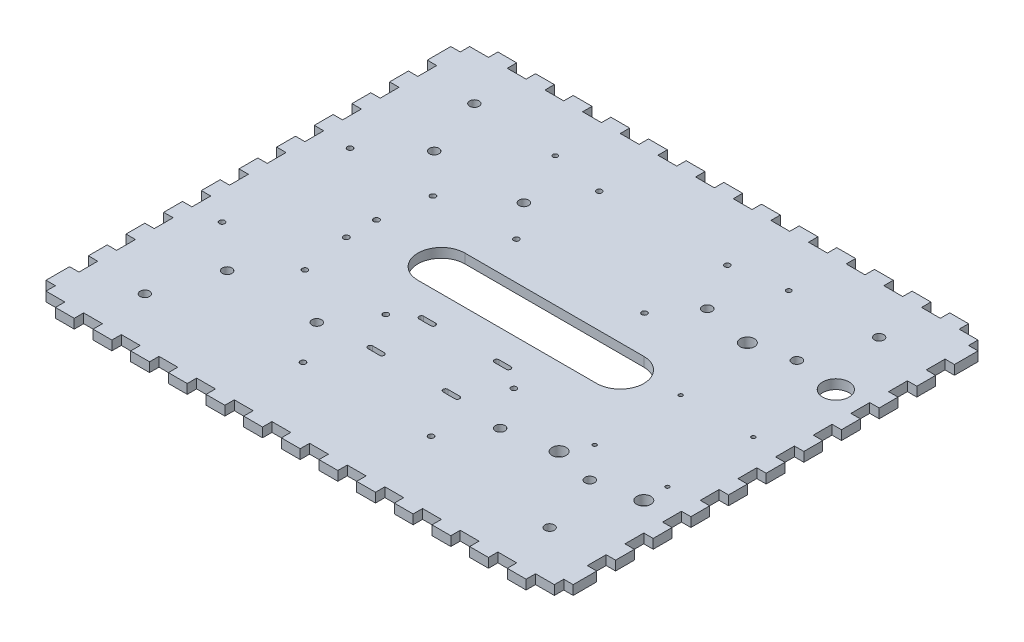
SolidWorks part; units mm, degrees
material "Acrylic (Medium-high impact)"
ref_plane "Front Plane" through (0, 0, 0) normal (0, 0, 1) x (1, 0, 0)
ref_plane "Top Plane" through (0, 0, 0) normal (0, 1, 0) x (1, 0, 0)
ref_plane "Right Plane" through (0, 0, 0) normal (1, 0, 0) x (0, 0, -1)
sketch "Sketch1" plane through (0, 0, 0) normal (0, 1, 0) x (1, 0, 0)
  line L0 (-144.4625, -95.25) -> (-42.8625, -95.25) construction
  line L2 (-174.625, -152.4) -> (-174.625, -139.7) construction
  line L3 (-174.625, 152.4) -> (-161.925, 152.4) construction
  line L4 (174.625, -152.4) -> (174.625, -133.5516) construction
  line L5 (-174.625, -152.4) -> (174.625, 152.4) construction
  line L6 (-174.625, 152.4) -> (174.625, -152.4) construction
  line L7 (-93.6625, -93.6625) -> (93.6625, -93.6625) construction
  line L8 (-93.6625, -93.6625) -> (-93.6625, 93.6625) construction
  line L9 (-93.6625, 93.6625) -> (93.6625, 93.6625) construction
  line L10 (93.6625, -93.6625) -> (93.6625, 93.6625) construction
  line L11 (-93.6625, -93.6625) -> (93.6625, 93.6625) construction
  line L12 (-93.6625, 93.6625) -> (93.6625, -93.6625) construction
  line L13 (42.8625, -95.25) -> (144.4625, -95.25) construction
  line L14 (-93.6625, -95.25) -> (-93.6625, -1.8183) construction
  line L15 (93.6625, -95.25) -> (93.6625, -91.9321) construction
  line L16 (-177.8, 0) -> (168.5824, 0) construction
  line L17 (42.8625, 95.25) -> (144.4625, 95.25) construction
  line L18 (93.6625, 95.25) -> (93.6625, 91.9321) construction
  line L19 (-93.6625, 95.25) -> (-93.6625, -1.8183) construction
  line L20 (-144.4625, 95.25) -> (-42.8625, 95.25) construction
  line L21 (-174.625, -152.4) -> (-161.925, -152.4) construction
  line L22 (-144.4625, 95.25) -> (-42.8625, 95.25) construction
  line L23 (-144.4625, 95.25) -> (-144.4625, 142.24) construction
  line L24 (-144.4625, 142.24) -> (-44.45, 142.24) construction
  line L26 (42.8625, 95.25) -> (144.4625, 95.25) construction
  line L28 (44.45, 142.24) -> (144.4625, 142.24) construction
  line L29 (144.4625, 95.25) -> (144.4625, 142.24) construction
  line L30 (44.45, 142.24) -> (-44.45, 142.24) construction
  line L31 (-144.4625, -95.25) -> (-42.8625, -95.25) construction
  line L33 (-144.4625, -142.24) -> (-42.8625, -142.24) construction
  line L34 (-42.8625, -95.25) -> (-42.8625, -142.24) construction
  line L35 (42.8625, -95.25) -> (144.4625, -95.25) construction
  line L36 (42.8625, -95.25) -> (42.8625, -142.24) construction
  line L37 (42.8625, -142.24) -> (144.4625, -142.24) construction
  line L43 (-110.3714, 54.9124) -> (-110.3714, 5.6364) construction
  line L44 (0.7937, 148.8037) -> (0.7938, -148.6976) construction
  line L45 (-174.625, 139.7) -> (-174.625, 152.4) construction
  line L46 (174.625, 133.5516) -> (174.625, 152.4) construction
  line L49 (163.5125, -152.4) -> (174.625, -152.4) construction
  line L50 (163.5125, 152.4) -> (174.625, 152.4) construction
  line L51 (144.4625, -95.25) -> (172.1593, -95.25) construction
  line L56 (156.9193, 27.9999) -> (71.9193, 27.9999) construction
  line L58 (-31.75, -142.24) -> (31.75, -142.24) construction
  line L62 (156.9193, 27.9999) -> (156.9193, -28.0001) construction
  line L64 (42.8625, -142.24) -> (-42.8625, -142.24) construction
  line L65 (-144.4625, -95.25) -> (-170.5718, -95.25) construction
  line L66 (-144.4625, 95.25) -> (-170.5718, 95.25) construction
  line L67 (144.4625, 95.25) -> (172.1593, 95.25) construction
  line L69 (-30.9562, -134.62) -> (32.5438, -134.62) construction
  line L73 (42.8625, 95.25) -> (-42.8625, 95.25) construction
  line L74 (42.8625, -95.25) -> (-42.8625, -95.25) construction
  line L75 (156.9193, -28.0001) -> (71.9193, -28.0001) construction
  line L76 (71.9193, 27.9999) -> (71.9193, -28.0001) construction
  line L81 (-113.5464, 54.9124) -> (-75.9544, 54.9124) construction
  line L82 (-113.5464, 54.9124) -> (-113.5464, 5.6364) construction
  line L83 (-113.5464, 5.6364) -> (-75.9544, 5.6364) construction
  line L84 (-75.9544, 54.9124) -> (-75.9544, 5.6364) construction
  line L85 (-79.1294, 5.6364) -> (-79.1294, 54.9124) construction
  line L87 (-177.8, -149.225) -> (177.8, -149.225)
  line L88 (-177.8, -149.225) -> (-177.8, 149.225)
  line L89 (-177.8, 149.225) -> (177.8, 149.225)
  line L90 (177.8, -149.225) -> (177.8, 149.225)
  line L91 (-177.8, -149.225) -> (177.8, 149.225) construction
  line L92 (-177.8, 149.225) -> (177.8, -149.225) construction
  arc A56 (-160.8077, 152.3508) -> (-174.5495, 138.3168) centre (-161.925, 139.7) ccw construction
  arc A57 (-160.7914, -152.3493) -> (-174.5495, -138.3168) centre (-161.925, -139.7) cw construction
  arc A58 (-174.5495, 138.3168) -> (-174.5495, -138.3168) centre (-1436.9949, 0) cw construction
  arc A59 (162.3789, -152.3493) -> (176.137, -138.3168) centre (163.5125, -139.7) ccw construction
  arc A60 (176.137, 138.3168) -> (176.137, -138.3168) centre (1438.5824, 0) ccw construction
  arc A61 (162.3952, 152.3508) -> (176.137, 138.3168) centre (163.5125, 139.7) cw construction
  arc A62 (-161.925, 152.4) -> (163.5125, 152.4) centre (0.7937, 3831.8037) ccw construction
  circle A64 centre (-161.925, 139.7) radius 1.8415 construction
  circle A65 centre (-161.925, -139.7) radius 1.8415 construction
  circle A66 centre (163.5125, -139.7) radius 1.8415 construction
  circle A67 centre (163.5125, 139.7) radius 1.8415 construction
  circle A82 centre (163.5125, 96.52) radius 1.8415 construction
  circle A84 centre (163.5125, -96.52) radius 1.8415 construction
  arc A88 (-170.5718, -95.25) -> (-170.5718, 95.25) centre (-1436.9949, 0) ccw construction
  arc A89 (172.1593, 95.25) -> (172.1593, -95.25) centre (1438.5824, 0) ccw construction
  circle A90 centre (-26.3525, -130.81) radius 1.905 construction
  circle A91 centre (29.5275, -130.81) radius 1.905 construction
  circle A98 centre (0, 0) radius 1.8415 construction
  circle A99 centre (-157.8718, 82.55) radius 1.8415 construction
  circle A100 centre (-157.8718, -82.55) radius 1.8415 construction
  circle A101 centre (159.4593, -82.55) radius 1.8415 construction
  circle A102 centre (159.4593, 82.55) radius 1.8415 construction
  circle A103 centre (-53.34, 0) radius 1.8415 construction
  circle A104 centre (-106.68, 0) radius 1.8415 construction
  circle A105 centre (-160.02, 0) radius 1.8415 construction
  circle A106 centre (-5.4718, -85.8596) radius 1.8415 construction
  circle A107 centre (7.0593, -85.8596) radius 1.8415 construction
  circle A108 centre (-8.6468, 82.55) radius 1.8415 construction
  circle A109 centre (10.2343, 82.55) radius 1.8415 construction
  circle A110 centre (75.4193, -24.5001) radius 1.651 construction
  circle A111 centre (75.4193, 24.5001) radius 1.651 construction
  circle A112 centre (133.4193, 24.5001) radius 1.651 construction
  circle A113 centre (133.4193, -24.5001) radius 1.651 construction
  circle A114 centre (-110.3714, 48.6894) radius 1.651 construction
  circle A115 centre (-110.3714, 42.3394) radius 1.651 construction
  circle A116 centre (-110.3714, 35.9894) radius 1.651 construction
  circle A117 centre (-110.3714, 29.6394) radius 1.651 construction
  circle A118 centre (-110.3714, 23.2894) radius 1.651 construction
  circle A119 centre (-110.3714, 16.9394) radius 1.651 construction
  circle A120 centre (-110.3714, 10.5894) radius 1.651 construction
  circle A121 centre (-79.1294, 48.6894) radius 1.651 construction
  circle A122 centre (-79.1294, 42.3394) radius 1.651 construction
  circle A123 centre (-79.1294, 35.9894) radius 1.651 construction
  circle A124 centre (-79.1294, 29.6394) radius 1.651 construction
  circle A125 centre (-79.1294, 23.2894) radius 1.651 construction
  circle A126 centre (-79.1294, 10.5894) radius 1.651 construction
  circle A127 centre (-79.1294, 16.9394) radius 1.651 construction
  circle A128 centre (-101.6, 10.16) radius 1.905
  circle A129 centre (-101.6, -10.16) radius 1.905
  point P0 (0, 0)
  point P6 (0, 0)
  point P37 (-93.6625, 79.4385)
  point P51 (-94.7504, 54.9124)
  point P188 (93.6625, 0)
  point P205 (0, -93.6625)
  dimension "D17" = 3.5
  dimension "D19" = 58
  dimension "D21" = 25.4
  dimension "D22" = 1270
  dimension "D23" = 3683
  dimension "D24" = 3.683
  dimension "D25" = 3.683
  dimension "D26" = 3.683
  dimension "D27" = 3.683
  dimension "D31" = 152.4
  dimension "D50" = 3.683
  dimension "D51" = 3.81
  dimension "D52" = 3.81
  dimension "D57" = 3.683
  dimension "D60" = 4
  dimension "D18" = 3.302
  dimension "D20" = 3.302
  dimension "D30" = 3.683
  dimension "D32" = 355.6
  dimension "D34" = 76.2
  dimension "D38" = 3.81
  dimension "D39" = 3.81
  dimension "D1" = 349.25
  dimension "D2" = 304.8
  dimension "D3" = 101.6
  dimension "D4" = 101.6
  dimension "D5" = 187.325
  dimension "D6" = 190.5
  dimension "D7" = 190.5
  dimension "D8" = 46.99
  dimension "D9" = 46.99
  dimension "D10" = 46.99
  dimension "D11" = 46.99
  dimension "D12" = 85
  dimension "D13" = 56
  dimension "D14" = 27.9999
  dimension "D15" = 15.24
  dimension "D16" = 3.5
  dimension "D28" = 4.953
  dimension "D29" = 6.35
  dimension "D33" = 298.45
  dimension "D35" = 76.2
  dimension "D36" = 20.32
  dimension "D37" = 139.065
  dimension "D40" = 63.5
  dimension "D41" = 31.75
  dimension "D43" = 7.62
  dimension "D44" = 46.99
  dimension "D45" = 19.05
  dimension "D46" = 45.72
  dimension "D47" = 19.05
  dimension "D53" = 3.81
  dimension "D55" = 3.81
  dimension "D58" = 12.7
  dimension "D59" = 12.7
  dimension "D61" = 53.34
extrude "Boss-Extrude1" add sketch "Sketch1" along normal blind 6.35
sketch "Sketch2" plane through (0, 6.35, 0) normal (0, 1, 0) x (1, 0, 0)
  line L0 (-61.8382, 69.85) -> (-122.3118, 69.85) construction
  line L1 (0, 0) -> (-61.8382, 0) construction
  line L2 (-61.8382, 0) -> (-61.8382, 69.85) construction
  line L4 (-61.8382, 0) -> (-61.8382, -69.85) construction
  line L5 (-61.8382, -69.85) -> (-122.3118, -69.85) construction
  line L6 (-61.8382, 69.85) -> (61.8382, 69.85) construction
  line L7 (-61.8382, -69.85) -> (61.8382, -69.85) construction
  line L8 (122.3118, 69.85) -> (61.8382, 69.85) construction
  line L9 (122.3118, -69.85) -> (61.8382, -69.85) construction
  line L10 (61.8382, 69.85) -> (61.8382, 0) construction
  line L11 (61.8382, 0) -> (61.8382, -69.85) construction
  line L12 (0, 0) -> (61.8382, 0) construction
  circle A8 centre (61.8382, -69.85) radius 3.2385
  circle A9 centre (122.3118, -69.85) radius 3.2385
  circle A10 centre (-122.3118, -69.85) radius 3.2385
  circle A11 centre (-61.8382, -69.85) radius 3.2385
  circle A12 centre (-122.3118, 69.85) radius 3.2385
  circle A13 centre (-61.8382, 69.85) radius 3.2385
  circle A14 centre (61.8382, 69.85) radius 3.2385
  circle A15 centre (122.3118, 69.85) radius 3.2385
  dimension "D4" = 6.477
  dimension "D1" = 69.85
  dimension "D2" = 61.8382
  dimension "D3" = 60.4736
extrude "Cut-Extrude1" cut sketch "Sketch2" against normal through all from surface at 0 starting at face at (0, 6.35, 0)
sketch "Sketch5" plane through (0, 6.35, 0) normal (0, 1, 0) x (-1, 0, 0)
  line L0 (-68.2625, -4.7625) -> (52.3875, -4.7625) construction
  line L1 (-68.2625, 11.1125) -> (52.3875, 11.1125)
  line L2 (-68.2625, -20.6375) -> (52.3875, -20.6375)
  arc A0 (-68.2625, 11.1125) -> (-68.2625, -20.6375) centre (-68.2625, -4.7625) ccw
  arc A1 (52.3875, -20.6375) -> (52.3875, 11.1125) centre (52.3875, -4.7625) ccw
  point P2 (-7.9375, -4.7625)
  dimension "D1" = 4.7625
  dimension "D2" = 7.9375
  dimension "D3" = 31.75
  dimension "D4" = 120.65
extrude "Cut-Extrude3" cut sketch "Sketch5" against normal through all
sketch "Sketch7" plane through (0, 6.35, 0) normal (0, 1, 0) x (1, 0, 0)
  line L0 (0, 0) -> (0, -49.022) construction
  line L3 (0, -49.022) -> (36.3871, -49.022) construction
  line L6 (-21.4312, -31.75) -> (21.4313, -31.75) construction
  line L7 (21.4313, -31.75) -> (29.3688, -31.75) construction
  line L8 (21.4313, -30.1625) -> (29.3687, -30.1625)
  line L9 (21.4313, -33.3375) -> (29.3687, -33.3375)
  line L12 (-21.4312, -31.75) -> (-29.3687, -31.75) construction
  line L15 (-21.4312, -30.1625) -> (-29.3687, -30.1625)
  line L16 (-21.4313, -33.3375) -> (-29.3687, -33.3375)
  line L17 (21.4312, -66.294) -> (29.3688, -66.294) construction
  line L18 (21.4313, -67.8815) -> (29.3687, -67.8815)
  line L19 (21.4313, -64.7065) -> (29.3687, -64.7065)
  line L20 (-21.4312, -66.294) -> (-29.3687, -66.294) construction
  line L21 (-21.4312, -67.8815) -> (-29.3687, -67.8815)
  line L22 (-21.4312, -64.7065) -> (-29.3687, -64.7065)
  arc A8 (21.4313, -30.1625) -> (21.4313, -33.3375) centre (21.4313, -31.75) ccw
  arc A9 (29.3687, -33.3375) -> (29.3687, -30.1625) centre (29.3688, -31.75) ccw
  arc A10 (-21.4312, -30.1625) -> (-21.4313, -33.3375) centre (-21.4312, -31.75) cw
  arc A11 (-29.3687, -33.3375) -> (-29.3687, -30.1625) centre (-29.3687, -31.75) cw
  arc A12 (21.4313, -67.8815) -> (21.4313, -64.7065) centre (21.4312, -66.294) cw
  arc A13 (29.3687, -64.7065) -> (29.3687, -67.8815) centre (29.3688, -66.294) cw
  arc A14 (-21.4312, -67.8815) -> (-21.4312, -64.7065) centre (-21.4312, -66.294) ccw
  arc A15 (-29.3687, -64.7065) -> (-29.3687, -67.8815) centre (-29.3687, -66.294) ccw
  point P5 (0, -31.75)
  point P6 (25.4, -31.75)
  point P13 (-25.4, -31.75)
  point P21 (25.4, -66.294)
  point P28 (-25.4, -66.294)
  dimension "D2" = 7.9375
  dimension "D1" = 1.5875
  dimension "D3" = 25.4
  dimension "D4" = 31.75
  dimension "D5" = 34.544
extrude "Cut-Extrude4" cut sketch "Sketch7" against normal through all
sketch "Sketch8" plane through (0, 6.35, 0) normal (0, 1, 0) x (1, 0, 0)
  line L0 (0, 0) -> (0, 63.5) construction
  line L1 (0, 63.5) -> (152.4, 63.5) construction
  line L2 (-149.4967, 0) -> (149.4967, 0) construction
  circle A1 centre (152.4, 63.5) radius 4.7625
  circle A2 centre (152.4, -63.5) radius 4.7625
  point P7 (0, 0)
  dimension "D1" = 63.5
  dimension "D3" = 9.525
  dimension "D2" = 152.4
extrude "Cut-Extrude5" cut sketch "Sketch8" against normal through all
pattern_linear "LPattern1" count 2 spacing 57.15 along (-1, 0, 0) of "Cut-Extrude5"
sketch "Sketch9" plane through (0, 6.35, 0) normal (0, 1, 0) x (1, 0, 0)
  line L1 (152.4, -47.625) -> (103.4001, -47.625) construction
  line L2 (152.4, -47.625) -> (152.4, 10.3749) construction
  line L3 (152.4, 10.3749) -> (103.4001, 10.3749) construction
  line L4 (103.4001, -47.625) -> (103.4001, 10.3749) construction
  line L5 (152.4, -47.625) -> (103.4001, 10.3749) construction
  line L6 (152.4, 10.3749) -> (103.4001, -47.625) construction
  circle A4 centre (103.4001, 10.3749) radius 1.27
  circle A5 centre (152.4, 10.3749) radius 1.27
  circle A6 centre (103.4001, -47.625) radius 1.27
  circle A7 centre (152.4, -47.625) radius 1.27
  point P0 (127.9, -18.6251)
  point P12 (152.4, -18.6251)
  dimension "D1" = 2.54
  dimension "D2" = 57.9999
  dimension "D3" = 48.9999
  dimension "D4" = 152.4
  dimension "D5" = 47.625
extrude "Cut-Extrude6" cut sketch "Sketch9" against normal through all
sketch "Sketch10" plane through (0, 6.35, 0) normal (0, 1, 0) x (1, 0, 0)
  line L0 (0, -69.85) -> (0, 0) construction
  line L1 (-46.99, -38.1) -> (46.99, -38.1) construction
  line L2 (-46.99, -38.1) -> (-46.99, -101.6) construction
  line L3 (-46.99, -101.6) -> (46.99, -101.6) construction
  line L4 (46.99, -38.1) -> (46.99, -101.6) construction
  line L5 (-46.99, -38.1) -> (46.99, -101.6) construction
  line L6 (-46.99, -101.6) -> (46.99, -38.1) construction
  line L7 (0, -69.85) -> (46.99, -69.85) construction
  circle A0 centre (-43.18, -41.91) radius 1.8415
  circle A1 centre (43.18, -41.91) radius 1.8415
  circle A2 centre (43.18, -97.79) radius 1.8415
  circle A3 centre (-43.18, -97.79) radius 1.8415
  point P0 (0, -69.85)
  dimension "D6" = 3.683
  dimension "D5" = 3.81
  dimension "D7" = 86.36
  dimension "D1" = 93.98
  dimension "D2" = 63.5
  dimension "D3" = 69.85
  dimension "D4" = 3.81
extrude "Cut-Extrude7" cut sketch "Sketch10" against normal through all
ref_plane "Plane1" through (0, 0, -2.1167) normal (0, 0, 1) x (1, 0, 0)
mirror "Mirror2" about plane through (0, 0, -2.1167) normal (0, 0, 1) of "Cut-Extrude7"
sketch "Sketch11" plane through (0, 6.35, 0) normal (0, 1, 0) x (1, 0, 0)
  line L0 (-124.46, 0) -> (0, 0) construction
  line L1 (-156.21, 46.99) -> (-92.71, 46.99) construction
  line L2 (-156.21, 46.99) -> (-156.21, -46.99) construction
  line L3 (-156.21, -46.99) -> (-92.71, -46.99) construction
  line L4 (-92.71, 46.99) -> (-92.71, -46.99) construction
  line L5 (-156.21, 46.99) -> (-92.71, -46.99) construction
  line L6 (-156.21, -46.99) -> (-92.71, 46.99) construction
  line L7 (-124.46, 0) -> (-124.46, 46.99) construction
  circle A0 centre (-152.4, 43.18) radius 1.8466
  circle A1 centre (-96.52, 43.18) radius 1.8466
  circle A2 centre (-96.52, -43.18) radius 1.8466
  circle A3 centre (-152.4, -43.18) radius 1.8466
  point P0 (-124.46, 0)
  dimension "D4" = 3.6932
  dimension "D5" = 3.81
  dimension "D6" = 3.81
  dimension "D1" = 63.5
  dimension "D2" = 93.98
  dimension "D3" = 124.46
extrude "Cut-Extrude8" cut sketch "Sketch11" against normal through all
sketch "Sketch13" plane through (0, 6.35, 0) normal (0, 1, 0) x (1, 0, 0)
  circle A0 centre (152.4, 66.04) radius 8.89
  dimension "D1" = 17.78
  dimension "D2" = 66.04
  dimension "D3" = 152.4
extrude "Cut-Extrude9" cut sketch "Sketch13" against normal through all
sketch "Sketch15" plane through (0, 6.35, 0) normal (0, 1, 0) x (1, 0, 0)
  line L0 (177.8, 149.225) -> (-177.8, 149.225) construction
  line L1 (146.05, 168.275) -> (133.35, 168.275)
  line L2 (146.05, 168.275) -> (146.05, 142.875)
  line L3 (146.05, 142.875) -> (133.35, 142.875)
  line L4 (133.35, 168.275) -> (133.35, 142.875)
  line L5 (146.05, 168.275) -> (133.35, 142.875) construction
  line L6 (146.05, 142.875) -> (133.35, 168.275) construction
  line L7 (177.8, -149.225) -> (177.8, 149.225) construction
  line L8 (120.65, 168.275) -> (107.95, 168.275)
  line L9 (120.65, 168.275) -> (120.65, 142.875)
  line L10 (120.65, 142.875) -> (107.95, 142.875)
  line L11 (107.95, 168.275) -> (107.95, 142.875)
  line L12 (120.65, 168.275) -> (107.95, 142.875) construction
  line L13 (120.65, 142.875) -> (107.95, 168.275) construction
  line L14 (95.25, 168.275) -> (82.55, 168.275)
  line L15 (95.25, 168.275) -> (95.25, 142.875)
  line L16 (95.25, 142.875) -> (82.55, 142.875)
  line L17 (82.55, 168.275) -> (82.55, 142.875)
  line L18 (95.25, 168.275) -> (82.55, 142.875) construction
  line L19 (95.25, 142.875) -> (82.55, 168.275) construction
  line L20 (69.85, 168.275) -> (57.15, 168.275)
  line L21 (69.85, 168.275) -> (69.85, 142.875)
  line L22 (69.85, 142.875) -> (57.15, 142.875)
  line L23 (57.15, 168.275) -> (57.15, 142.875)
  line L24 (69.85, 168.275) -> (57.15, 142.875) construction
  line L25 (69.85, 142.875) -> (57.15, 168.275) construction
  line L26 (44.45, 168.275) -> (31.75, 168.275)
  line L27 (44.45, 168.275) -> (44.45, 142.875)
  line L28 (44.45, 142.875) -> (31.75, 142.875)
  line L29 (31.75, 168.275) -> (31.75, 142.875)
  line L30 (44.45, 168.275) -> (31.75, 142.875) construction
  line L31 (44.45, 142.875) -> (31.75, 168.275) construction
  line L32 (19.05, 168.275) -> (6.35, 168.275)
  line L33 (19.05, 168.275) -> (19.05, 142.875)
  line L34 (19.05, 142.875) -> (6.35, 142.875)
  line L35 (6.35, 168.275) -> (6.35, 142.875)
  line L36 (19.05, 168.275) -> (6.35, 142.875) construction
  line L37 (19.05, 142.875) -> (6.35, 168.275) construction
  line L38 (-6.35, 168.275) -> (-19.05, 168.275)
  line L39 (-6.35, 168.275) -> (-6.35, 142.875)
  line L40 (-6.35, 142.875) -> (-19.05, 142.875)
  line L41 (-19.05, 168.275) -> (-19.05, 142.875)
  line L42 (-6.35, 168.275) -> (-19.05, 142.875) construction
  line L43 (-6.35, 142.875) -> (-19.05, 168.275) construction
  line L44 (-31.75, 168.275) -> (-44.45, 168.275)
  line L45 (-31.75, 168.275) -> (-31.75, 142.875)
  line L46 (-31.75, 142.875) -> (-44.45, 142.875)
  line L47 (-44.45, 168.275) -> (-44.45, 142.875)
  line L48 (-31.75, 168.275) -> (-44.45, 142.875) construction
  line L49 (-31.75, 142.875) -> (-44.45, 168.275) construction
  line L50 (-57.15, 168.275) -> (-69.85, 168.275)
  line L51 (-57.15, 168.275) -> (-57.15, 142.875)
  line L52 (-57.15, 142.875) -> (-69.85, 142.875)
  line L53 (-69.85, 168.275) -> (-69.85, 142.875)
  line L54 (-57.15, 168.275) -> (-69.85, 142.875) construction
  line L55 (-57.15, 142.875) -> (-69.85, 168.275) construction
  line L56 (-82.55, 168.275) -> (-95.25, 168.275)
  line L57 (-82.55, 168.275) -> (-82.55, 142.875)
  line L58 (-82.55, 142.875) -> (-95.25, 142.875)
  line L59 (-95.25, 168.275) -> (-95.25, 142.875)
  line L60 (-82.55, 168.275) -> (-95.25, 142.875) construction
  line L61 (-82.55, 142.875) -> (-95.25, 168.275) construction
  line L62 (-107.95, 168.275) -> (-120.65, 168.275)
  line L63 (-107.95, 168.275) -> (-107.95, 142.875)
  line L64 (-107.95, 142.875) -> (-120.65, 142.875)
  line L65 (-120.65, 168.275) -> (-120.65, 142.875)
  line L66 (-107.95, 168.275) -> (-120.65, 142.875) construction
  line L67 (-107.95, 142.875) -> (-120.65, 168.275) construction
  line L68 (-133.35, 168.275) -> (-146.05, 168.275)
  line L69 (-133.35, 168.275) -> (-133.35, 142.875)
  line L70 (-133.35, 142.875) -> (-146.05, 142.875)
  line L71 (-146.05, 168.275) -> (-146.05, 142.875)
  line L72 (-133.35, 168.275) -> (-146.05, 142.875) construction
  line L73 (-133.35, 142.875) -> (-146.05, 168.275) construction
  line L78 (-177.8, 149.225) -> (-177.8, -149.225) construction
  line L84 (-184.15, 168.275) -> (-158.75, 168.275)
  line L85 (-184.15, 168.275) -> (-184.15, 142.875)
  line L86 (-158.75, 168.275) -> (-171.45, 168.275) [skipped]
  line L87 (-158.75, 168.275) -> (-158.75, 142.875) [skipped]
  line L88 (-158.75, 142.875) -> (-171.45, 142.875) [skipped]
  line L89 (-171.45, 168.275) -> (-171.45, 142.875) [skipped]
  line L90 (-184.15, 168.275) -> (-196.85, 168.275) [skipped]
  line L91 (-184.15, 168.275) -> (-184.15, 142.875) [skipped]
  line L92 (-184.15, 142.875) -> (-196.85, 142.875) [skipped]
  line L93 (-196.85, 168.275) -> (-196.85, 142.875) [skipped]
  line L94 (-158.75, 168.275) -> (-171.45, 142.875) construction
  line L95 (-158.75, 142.875) -> (-171.45, 168.275) construction
  line L96 (-184.15, 168.275) -> (-196.85, 142.875) construction
  line L97 (-184.15, 142.875) -> (-196.85, 168.275) construction
  line L98 (-184.15, 142.875) -> (-158.75, 142.875)
  line L99 (-158.75, 168.275) -> (-158.75, 142.875)
  line L100 (-184.15, 168.275) -> (-158.75, 142.875) construction
  line L101 (-184.15, 142.875) -> (-158.75, 168.275) construction
  line L102 (184.15, 168.275) -> (158.75, 168.275)
  line L103 (184.15, 168.275) -> (184.15, 142.875)
  line L104 (184.15, 142.875) -> (158.75, 142.875)
  line L105 (158.75, 168.275) -> (158.75, 142.875)
  line L106 (184.15, 168.275) -> (158.75, 142.875) construction
  line L107 (184.15, 142.875) -> (158.75, 168.275) construction
  point P0 (139.7, 155.575)
  point P9 (-190.5, 155.575)
  point P10 (-165.1, 155.575)
  point P11 (114.3, 155.575)
  point P16 (88.9, 155.575)
  point P21 (63.5, 155.575)
  point P26 (38.1, 155.575)
  point P31 (12.7, 155.575)
  point P36 (-12.7, 155.575)
  point P41 (-38.1, 155.575)
  point P46 (-63.5, 155.575)
  point P51 (-88.9, 155.575)
  point P56 (-114.3, 155.575)
  point P61 (-139.7, 155.575)
  point P68 (-171.45, 155.575)
  point P73 (171.45, 155.575)
  dimension "D1" = 6.35
  dimension "D2" = 31.75
  dimension "D3" = 12.7
  dimension "D4" = 25.4
  dimension "D6" = 31.75
  dimension "D7" = 19.05
  dimension "D8" = 6.35
  dimension "D9" = 25.4
  dimension "D10" = 25.4
  dimension "D11" = 6.35
  dimension "D12" = 19.05
  dimension "D13" = 25.4
  dimension "D14" = 25.4
  dimension "D5" = 14
sketch "Sketch16" plane through (0, 6.35, 0) normal (0, 1, 0) x (1, 0, 0)
  line L0 (177.8, 149.225) -> (165.1, 149.225) construction
  line L1 (196.85, 120.65) -> (171.45, 120.65)
  line L2 (196.85, 120.65) -> (196.85, 107.95)
  line L3 (196.85, 107.95) -> (171.45, 107.95)
  line L4 (171.45, 120.65) -> (171.45, 107.95)
  line L5 (196.85, 120.65) -> (171.45, 107.95) construction
  line L6 (196.85, 107.95) -> (171.45, 120.65) construction
  line L7 (177.8, -149.225) -> (177.8, 149.225) construction
  point P0 (184.15, 114.3)
  dimension "D1" = 28.575
  dimension "D2" = 6.35
  dimension "D3" = 12.7
  dimension "D4" = 25.4
extrude "Cut-Extrude19" cut sketch "Sketch16" against normal through all both and the other way through all
pattern_linear "LPattern2" count 10 spacing 25.4 along (0, 0, 1) of "Cut-Extrude19"
mirror "Mirror4" about plane through (0, 0, 0) normal (1, 0, 0) of "Cut-Extrude19", "LPattern2"
sketch "Sketch17" plane through (0, 6.35, 0) normal (0, 1, 0) x (1, 0, 0)
  line L1 (-136.525, -111.125) -> (136.525, -111.125) construction
  line L2 (-136.525, -111.125) -> (-136.525, 111.125) construction
  line L3 (-136.525, 111.125) -> (136.525, 111.125) construction
  line L4 (136.525, -111.125) -> (136.525, 111.125) construction
  line L5 (-136.525, -111.125) -> (136.525, 111.125) construction
  line L6 (-136.525, 111.125) -> (136.525, -111.125) construction
  circle A0 centre (-136.525, 111.125) radius 3.175
  circle A1 centre (136.525, 111.125) radius 3.175
  circle A2 centre (136.525, -111.125) radius 3.175
  circle A3 centre (-136.525, -111.125) radius 3.175
  point P0 (0, 0)
  dimension "D3" = 6.35
  dimension "D1" = 273.05
  dimension "D2" = 222.25
extrude "Cut-Extrude20" cut sketch "Sketch17" against normal through all
sketch "Sketch18" plane through (0, 6.35, 0) normal (0, 1, 0) x (1, 0, 0)
  line L0 (177.8, 149.225) -> (-177.8, 149.225) construction
  line L1 (196.85, 161.925) -> (171.45, 161.925)
  line L2 (196.85, 161.925) -> (196.85, 136.525)
  line L3 (196.85, 136.525) -> (171.45, 136.525)
  line L4 (171.45, 161.925) -> (171.45, 136.525)
  line L5 (196.85, 161.925) -> (171.45, 136.525) construction
  line L6 (196.85, 136.525) -> (171.45, 161.925) construction
  line L7 (177.8, 120.65) -> (177.8, 149.225) construction
  line L8 (0, -3.4925) -> (0, 3.4925) construction
  line L9 (-196.85, 136.525) -> (-171.45, 161.925) construction
  line L10 (-196.85, 161.925) -> (-171.45, 136.525) construction
  line L11 (-171.45, 161.925) -> (-171.45, 136.525)
  line L12 (-196.85, 136.525) -> (-171.45, 136.525)
  line L13 (-196.85, 161.925) -> (-196.85, 136.525)
  line L14 (-196.85, 161.925) -> (-171.45, 161.925)
  line L15 (-3.4925, 0) -> (3.4925, 0) construction
  line L16 (196.85, -136.525) -> (171.45, -161.925) construction
  line L17 (196.85, -161.925) -> (171.45, -136.525) construction
  line L18 (171.45, -161.925) -> (171.45, -136.525)
  line L19 (196.85, -136.525) -> (171.45, -136.525)
  line L20 (196.85, -161.925) -> (196.85, -136.525)
  line L21 (196.85, -161.925) -> (171.45, -161.925)
  line L22 (-196.85, -161.925) -> (-171.45, -136.525) construction
  line L23 (-196.85, -136.525) -> (-171.45, -161.925) construction
  line L24 (-196.85, -161.925) -> (-171.45, -161.925)
  line L25 (-196.85, -161.925) -> (-196.85, -136.525)
  line L26 (-196.85, -136.525) -> (-171.45, -136.525)
  line L27 (-171.45, -161.925) -> (-171.45, -136.525)
  point P0 (184.15, 149.225)
  point P15 (-184.15, 149.225)
  point P22 (184.15, -149.225)
  point P27 (-184.15, -149.225)
  dimension "D1" = 12.7
  dimension "D2" = 6.35
  dimension "D3" = 25.4
  dimension "D4" = 25.4
extrude "Cut-Extrude21" cut sketch "Sketch18" against normal through all
extrude "Cut-Extrude22" cut sketch "Sketch15" against normal through all
mirror "Mirror5" about plane through (0, 0, 0) normal (0, 0, 1) of "Cut-Extrude22"
sketch "Sketch19" plane through (0, 6.35, 0) normal (0, 1, 0) x (1, 0, 0)
  line L0 (0, 0) -> (0, 107.95) construction
  line L1 (78.74, 107.95) -> (-78.74, 107.95) construction
  circle A0 centre (-78.74, 107.95) radius 1.6002
  circle A1 centre (78.74, 107.95) radius 1.6002
  point P5 (0, 107.95)
  dimension "D2" = 3.2004
  dimension "D1" = 157.48
  dimension "D3" = 107.95
extrude "Cut-Extrude23" cut sketch "Sketch19" against normal through all
